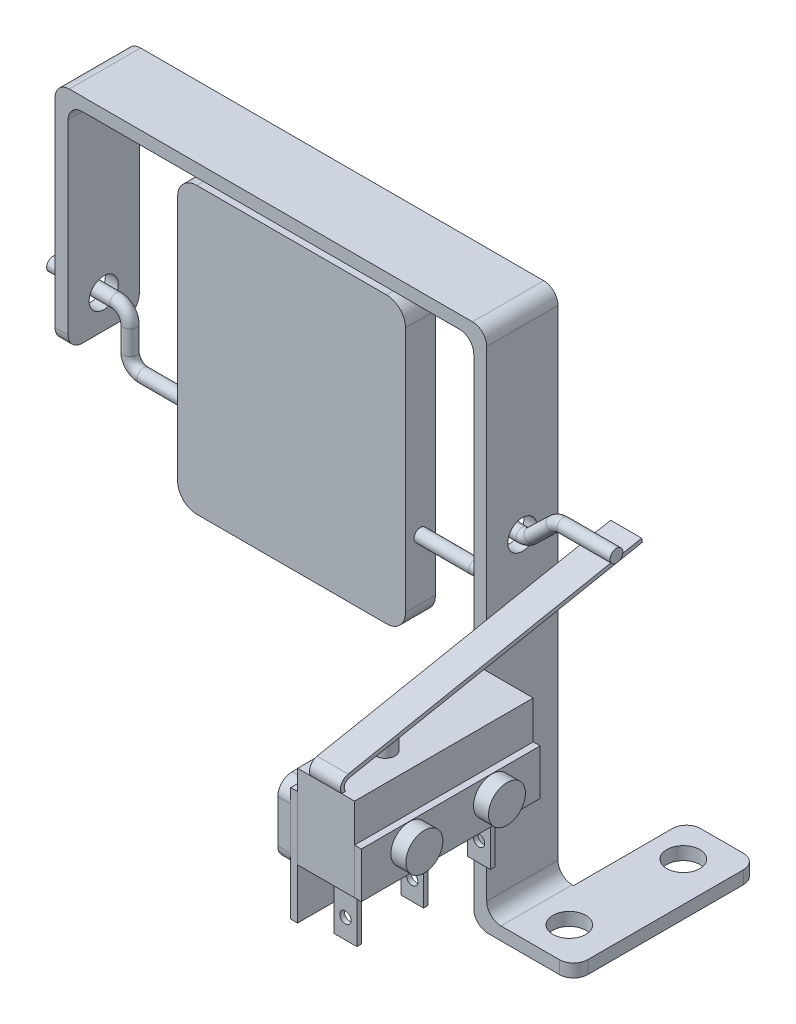
SolidWorks part; units mm, degrees
ref_plane "Front Plane" through (0, 0, 0) normal (0, 0, 1) x (1, 0, 0)
ref_plane "Top Plane" through (0, 0, 0) normal (0, 1, 0) x (1, 0, 0)
ref_plane "Right Plane" through (0, 0, 0) normal (1, 0, 0) x (0, 0, -1)
sketch "Sketch1" plane through (0, 0, 0) normal (0, 0, 1) x (1, 0, 0)
  line L0 (0, 0) -> (-11.1252, 0)
  line L1 (-11.1252, 0) -> (-11.1252, 56.7182)
  line L2 (-11.1252, 56.7182) -> (-56.3372, 56.7182)
  line L3 (-56.3372, 56.7182) -> (-56.3372, 32.766)
  line L4 (-56.3372, 32.766) -> (-57.785, 32.766)
  line L5 (-57.785, 32.766) -> (-57.785, 58.166)
  line L6 (-57.785, 58.166) -> (-9.6774, 58.166)
  line L7 (-9.6774, 58.166) -> (-9.6774, 1.4478)
  line L8 (-9.6774, 1.4478) -> (0, 1.4478)
  line L9 (0, 1.4478) -> (0, 0)
  line L10 (-11.1252, 56.7182) -> (-11.1252, 58.166) construction
  line L11 (-11.1252, 56.7182) -> (-9.6774, 56.7182) construction
  dimension "D1" = 45.212
  dimension "D2" = 1.4478
  dimension "D3" = 58.166
  dimension "D4" = 11.1252
  dimension "D5" = 25.4
extrude "Boss-Extrude1" add sketch "Sketch1" along normal mid plane 7.9375
sketch "Sketch2" plane through (0, 1.4478, 0) normal (0, 1, 0) x (1, 0, 0)
  line L0 (0, -3.9688) -> (0, 3.9688) construction
  line L1 (0, 3.9688) -> (-7.9375, 3.9687)
  line L2 (0, 3.9688) -> (0, 16.5545)
  line L3 (0, 16.5545) -> (-7.9375, 16.5544)
  line L4 (-7.9375, 3.9687) -> (-7.9375, 16.5544)
  line L5 (0, -3.9688) -> (-9.6774, -3.9688) construction
  dimension "D1" = 20.5232
extrude "Boss-Extrude2" add sketch "Sketch2" against normal up to surface (1.4478 mm away) up to face at (-5.5626, 0, 0)
sketch "Sketch13" plane through (0, 1.4478, 0) normal (0, 1, 0) x (1, 0, 0)
  line L1 (-2.54, 12.6429) -> (0, 12.6429) construction
  line L2 (0, -3.9688) -> (0, 16.5545) construction
  line L3 (0, 6.2929) -> (-7.9375, 6.2929) construction
  line L4 (-7.9375, 16.5544) -> (-7.9375, 3.9687) construction
  circle A0 centre (-4.3815, 12.6429) radius 1.8415
  circle A1 centre (-4.3815, -0.0571) radius 1.8415
  dimension "D1" = 3.683
  dimension "D2" = 12.7
  dimension "D3" = 2.54
extrude "Cut-Extrude3" cut sketch "Sketch13" against normal through all
ref_plane "Plane1" through (0, 19.5326, 0) normal (0, 1, 0) x (1, 0, 0)
sketch "Sketch3" plane through (0, 19.5326, 0) normal (0, 1, 0) x (1, 0, 0)
  line L0 (-9.6774, -3.9688) -> (-9.6774, -5.1943)
  line L1 (-9.6774, -3.9688) -> (-11.1252, -3.9688)
  line L2 (-9.6774, -3.9688) -> (-57.785, -3.9688) construction
  line L3 (-11.1252, -3.9688) -> (-11.1252, -5.5563)
  line L4 (-9.6774, -5.1943) -> (-7.1374, -9.9568)
  line L5 (-7.1374, -9.9568) -> (-7.1374, -28.3528)
  line L6 (-11.1252, -5.5563) -> (-8.5852, -10.3187)
  line L7 (-8.5852, -10.3187) -> (-8.5852, -28.3528)
  line L8 (-8.5852, -28.3528) -> (-7.1374, -28.3528)
  line L9 (-8.4074, -7.5755) -> (-9.6849, -8.2569) construction
  line L10 (0, -3.9688) -> (-9.6774, -3.9688) construction
  dimension "D1" = 24.384
  dimension "D2" = 2.54
  dimension "D3" = 6.35
  dimension "D4" = 1.5875
extrude "Boss-Extrude3" add sketch "Sketch3" along normal blind 7.9375
sketch "Sketch12" plane through (-57.785, 0, 0) normal (-1, 0, 0) x (0, 0, 1)
  line L0 (3.9688, 32.766) -> (-3.9688, 32.766) construction
  circle A0 centre (0, 36.449) radius 1.6256
  point P4 (0, 32.766)
  dimension "D1" = 3.2512
  dimension "D2" = 3.683
extrude "Cut-Extrude2" cut sketch "Sketch12" against normal through all
fillet "Fillet1" radius 1.5875 13 edges at (-7.8613, 19.5326, 28.3528) (-7.8613, 27.4701, 28.3528) (0, 0.7239, 3.9688) (0, 0.7239, -16.5545) (-7.9375, 0.7239, -16.5544) (-57.0611, 32.766, -3.9688) (-57.0611, 32.766, 3.9688) (-11.1252, 56.7182, 0) (-56.3372, 56.7182, 0) (-11.1252, 0, 0) (-9.6774, 1.4478, 0) (-9.6774, 58.166, 0) (-57.785, 58.166, 0)
sketch "Sketch5" plane through (-7.1374, 0, 0) normal (1, 0, 0) x (0, 0, -1)
  line L0 (-28.3528, 25.8826) -> (-28.3528, 21.1201) construction
  line L1 (-28.3528, 27.4701) -> (-7.5248, 27.4701)
  line L2 (-28.3528, 27.4701) -> (-28.3528, 14.7701)
  line L3 (-28.3528, 14.7701) -> (-7.5248, 14.7701)
  line L4 (-7.5248, 27.4701) -> (-7.5248, 14.7701)
  line L5 (-26.7653, 27.4701) -> (-9.9568, 27.4701) construction
  dimension "D1" = 12.7
  dimension "D2" = 20.828
extrude "Boss-Extrude5" add sketch "Sketch5" along normal blind 0.762 separate body
sketch "Sketch4" plane through (-6.3754, 0, 0) normal (1, 0, 0) x (0, 0, -1)
  line L0 (-28.3528, 25.8826) -> (-28.3528, 21.1201) construction
  line L1 (-28.3528, 29.718) -> (-8.4392, 29.718)
  line L2 (-28.3528, 29.718) -> (-28.3528, 20.3962)
  line L3 (-28.3528, 20.3962) -> (-8.4392, 20.3962)
  line L4 (-8.4392, 29.718) -> (-8.4392, 20.3962)
  line L6 (-26.7653, 27.4701) -> (-9.9568, 27.4701) construction
  dimension "D1" = 19.9136
  dimension "D2" = 9.3218
  dimension "D3" = 2.2479
extrude "Boss-Extrude4" add sketch "Sketch4" along normal blind 6.35 separate body
sketch "Sketch6" plane through (-0.0254, 0, 0) normal (1, 0, 0) x (0, 0, -1)
  line L0 (-8.4392, 20.3962) -> (-8.4392, 29.718) construction
  line L1 (-28.3528, 20.3962) -> (-8.4392, 20.3962)
  line L2 (-28.3528, 20.3962) -> (-28.3528, 25.4762)
  line L3 (-28.3528, 25.4762) -> (-8.4392, 25.4762)
  line L4 (-8.4392, 20.3962) -> (-8.4392, 25.4762)
  dimension "D1" = 5.08
extrude "Boss-Extrude6" add sketch "Sketch6" along normal blind 0.762 separate body
sketch "Sketch7" plane through (0.7366, 0, 0) normal (1, 0, 0) x (0, 0, -1)
  line L0 (-8.4392, 25.4762) -> (-28.3528, 25.4762) construction
  line L1 (-18.396, 25.4762) -> (-18.396, 14.7701) construction
  line L2 (-28.3528, 14.7701) -> (-7.5248, 14.7701) construction
  circle A0 centre (-22.9997, 23.3807) radius 2.0638
  circle A1 centre (-13.7922, 23.3807) radius 2.0638
  dimension "D1" = 4.1275
  dimension "D2" = 2.0955
  dimension "D3" = 9.2075
extrude "Boss-Extrude7" add sketch "Sketch7" along normal blind 1.6637
ref_plane "Plane2" through (-2.032, 0, 0) normal (1, 0, 0) x (0, 0, -1)
sketch "Sketch8" plane through (-2.032, 0, 0) normal (1, 0, 0) x (0, 0, -1)
  line L0 (-28.3528, 20.3962) -> (-8.4392, 20.3962) construction
  line L1 (-26.0922, 20.3962) -> (-25.5842, 20.3962)
  line L2 (-26.0922, 20.3962) -> (-26.0922, 13.5382)
  line L3 (-26.0922, 13.5382) -> (-25.5842, 13.5382)
  line L4 (-25.5842, 20.3962) -> (-25.5842, 13.5382)
  line L5 (-18.396, 25.4762) -> (-18.396, 14.7701) construction
  line L6 (-18.65, 20.3962) -> (-18.142, 20.3962)
  line L7 (-18.65, 20.3962) -> (-18.65, 13.5382)
  line L8 (-18.65, 13.5382) -> (-18.1419, 13.5382)
  line L9 (-18.142, 20.3962) -> (-18.1419, 13.5382)
  line L10 (-11.2077, 20.3962) -> (-10.6997, 20.3962)
  line L11 (-11.2077, 20.3962) -> (-11.2077, 13.5382)
  line L12 (-11.2077, 13.5382) -> (-10.6997, 13.5382)
  line L13 (-10.6997, 20.3962) -> (-10.6997, 13.5382)
  line L14 (-8.4392, 25.4762) -> (-28.3528, 25.4762) construction
  line L15 (-28.3528, 14.7701) -> (-7.5248, 14.7701) construction
  point P14 (-18.396, 20.3962)
  dimension "D1" = 0.508
  dimension "D2" = 6.858
  dimension "D3" = 6.9342
extrude "Boss-Extrude8" add sketch "Sketch8" against normal blind 2.54
sketch "Sketch9" plane through (0, 0, 26.0922) normal (0, 0, 1) x (1, 0, 0)
  line L0 (-4.572, 13.5382) -> (-2.032, 13.5382) construction
  circle A0 centre (-3.302, 15.7226) radius 0.635
  point P4 (-3.302, 13.5382)
  dimension "D1" = 1.27
  dimension "D2" = 2.1844
extrude "Cut-Extrude1" cut sketch "Sketch9" against normal through all
ref_plane "Plane3" through (-3.2004, 0, 0) normal (1, 0, 0) x (0, 0, -1)
sketch "Sketch10" plane through (-3.2004, 0, 0) normal (1, 0, 0) x (0, 0, -1)
  line L0 (-27.5395, 30.8058) -> (5.1752, 37.2193)
  line L1 (5.1752, 37.2193) -> (5.0897, 37.6555)
  line L2 (5.0897, 37.6555) -> (-27.625, 31.242)
  line L3 (-27.625, 31.242) -> (-27.5395, 30.8058) construction
  line L4 (-8.4392, 29.718) -> (-28.3528, 29.718) construction
  line L5 (-8.4392, 20.3962) -> (-8.4392, 29.718) construction
  line L6 (-27.9082, 29.718) -> (-28.3528, 29.718)
  line L7 (-28.372, 30.6629) -> (-27.9709, 30.4714) construction
  line L8 (-28.4678, 30.4624) -> (-28.2762, 30.8635) construction
  arc A0 (-28.3528, 29.718) -> (-27.625, 31.242) centre (-27.4226, 30.2096) cw
  arc A1 (-27.5395, 30.8058) -> (-27.9082, 29.718) centre (-27.3702, 30.142) ccw
  point P17 (-28.372, 30.6629)
  dimension "D1" = 33.3375
  dimension "D2" = 0.4445
  dimension "D3" = 7.9375
  dimension "D4" = 1.524
  dimension "D5" = 13.6144
extrude "Boss-Extrude9" add sketch "Sketch10" along normal mid plane 3.4544
sketch "Sketch11" plane through (0, 29.718, 0) normal (0, 1, 0) x (1, 0, 0)
  line L0 (-0.0254, -8.4392) -> (-6.3754, -8.4392) construction
  line L1 (-0.0254, -28.3528) -> (-6.3754, -28.3528) construction
  circle A0 centre (-3.2004, -21.7488) radius 1.0795
  point P5 (-3.2004, -8.4392)
  dimension "D1" = 2.159
  dimension "D2" = 6.604
extrude "Boss-Extrude10" add sketch "Sketch11" along normal up to surface (2.0114 mm away)
sketch3d "3DSketch1"
  line L0 (-61.976, 36.449, 0) -> (-54.9402, 36.449, 0)
  line L1 (-33.7312, 53.6702, 0) -> (-33.7312, 56.7182, 0) construction
  line L2 (-53.4162, 34.925, 0) -> (-53.4162, 32.258, 0)
  line L3 (-54.7497, 56.7182, 3.9688) -> (-12.7127, 56.7182, 3.9688) construction
  line L4 (-46.4312, 53.6702, 0) -> (-21.0312, 53.6702, 0) construction
  line L5 (-46.4312, 53.6702, 0) -> (-46.4312, 21.9202, 0) construction
  line L6 (-46.4312, 21.9202, 0) -> (-21.0312, 21.9202, 0) construction
  line L7 (-21.0312, 53.6702, 0) -> (-21.0312, 21.9202, 0) construction
  line L8 (-51.8922, 30.734, 0) -> (-46.4312, 30.734, 0)
  line L9 (-46.4312, 30.734, 0) -> (-21.0312, 30.734, 0)
  line L10 (-21.0312, 30.734, 0) -> (-14.9352, 30.734, 0)
  line L11 (-13.4112, 32.258, 0) -> (-13.4112, 34.925, 0)
  line L12 (-11.8872, 36.449, 0) -> (-9.6774, 36.449, 0)
  line L13 (-8.6221, 36.8735, 0) -> (-6.1722, 39.2249, 0)
  line L14 (-5.1169, 39.6494, 0) -> (0.8128, 39.6494, 0)
  arc A0 (-14.9352, 30.734, 0) -> (-13.4112, 32.258, 0) centre (-14.9352, 32.258, 0) cw
  arc A1 (-54.9402, 36.449, 0) -> (-53.4162, 34.925, 0) centre (-54.9402, 34.925, 0) cw
  arc A2 (-53.4162, 32.258, 0) -> (-51.8922, 30.734, 0) centre (-51.8922, 32.258, 0) cw
  arc A3 (-13.4112, 34.925, 0) -> (-11.8872, 36.449, 0) centre (-11.8872, 34.925, 0) cw
  arc A4 (-9.6774, 36.449, 0) -> (-8.6221, 36.8735, 0) centre (-9.6774, 37.973, 0) cw
  arc A5 (-6.1722, 39.2249, 0) -> (-5.1169, 39.6494, 0) centre (-5.1169, 38.1254, 0) cw
  point P4 (-54.9402, 34.925, -1.524)
  point P7 (-51.8922, 32.258, 1.524)
  point P19 (-33.7312, 56.7182, 3.9688)
  point P21 (-14.9352, 32.258, 1.524)
  point P26 (-11.8872, 34.925, -1.524)
  point P30 (-9.6774, 37.973, 1.524)
  point P34 (-5.1169, 38.1254, -1.524)
  dimension "D1" = 4.191
  dimension "D2" = 25.4
  dimension "D3" = 31.75
  dimension "D4" = 3.048
  dimension "D5" = 6.985
  dimension "D6" = 5.715
  dimension "D7" = 1.524
  dimension "D8" = 7.62
  dimension "D9" = 2.286
  dimension "D10" = 3.2004
  dimension "D11" = 3.5052
ref_plane "Plane4" through (-61.976, 0, 0) normal (-1, 0, 0) x (0, 0, 1)
sketch "Sketch15" plane through (-61.976, 0, 0) normal (-1, 0, 0) x (0, 0, 1)
  circle A0 centre (0, 36.449) radius 0.7176
  dimension "D1" = 1.4351
sweep "Sweep1" add profiles "Sketch15" path "3DSketch1"
sketch "Sketch16" plane through (0, 0, 0) normal (0, 0, 1) x (1, 0, 0)
  line L0 (-46.4312, 53.6702) -> (-46.4312, 21.9202) construction
  line L1 (-46.4312, 21.9202) -> (-21.0312, 21.9202) construction
  line L2 (-21.0312, 53.6702) -> (-21.0312, 21.9202) construction
  line L3 (-46.4312, 53.6702) -> (-21.0312, 53.6702) construction
  line L4 (-46.4312, 51.5366) -> (-46.4312, 24.0538)
  line L5 (-44.2976, 21.9202) -> (-23.1648, 21.9202)
  line L6 (-21.0312, 51.5366) -> (-21.0312, 24.0538)
  line L7 (-44.2976, 53.6702) -> (-23.1648, 53.6702)
  arc A0 (-46.4312, 24.0538) -> (-44.2976, 21.9202) centre (-44.2976, 24.0538) ccw
  arc A1 (-23.1648, 21.9202) -> (-21.0312, 24.0538) centre (-23.1648, 24.0538) ccw
  arc A2 (-21.0312, 51.5366) -> (-23.1648, 53.6702) centre (-23.1648, 51.5366) ccw
  arc A3 (-46.4312, 51.5366) -> (-44.2976, 53.6702) centre (-44.2976, 51.5366) cw
  dimension "D1" = 2.1336
extrude "Boss-Extrude11" add sketch "Sketch16" along normal mid plane 3.3274
ref_plane "Plane5" through (-33.7312, 0, 0) normal (1, 0, 0) x (0, 0, -1)
ref_plane "Plane6" through (3.2006, 0, -14.4371) normal (0.2164, 0, -0.9763) x (0, 1, 0)
sketch "Sketch17" plane through (0, 0, 0) normal (0, 1, 0) x (1, 0, 0)
  line L0 (-11.2649, 0) -> (-14.9674, 0)
  line L1 (-11.2649, -3.9688) -> (-11.2649, 3.9688) construction
  dimension "D1" = 3.7025
sketch "Sketch18" plane through (0, 0, 1.6637) normal (0, 0, 1) x (1, 0, 0)
  line L0 (50.3505, 315.588) -> (437.6838, 315.588) construction
sketch "Sketch19" plane through (0, 0, -1.6637) normal (0, 0, -1) x (-1, 0, 0)
  line L0 (104.6373, 413.5227) -> (425.3039, 413.5227) construction
